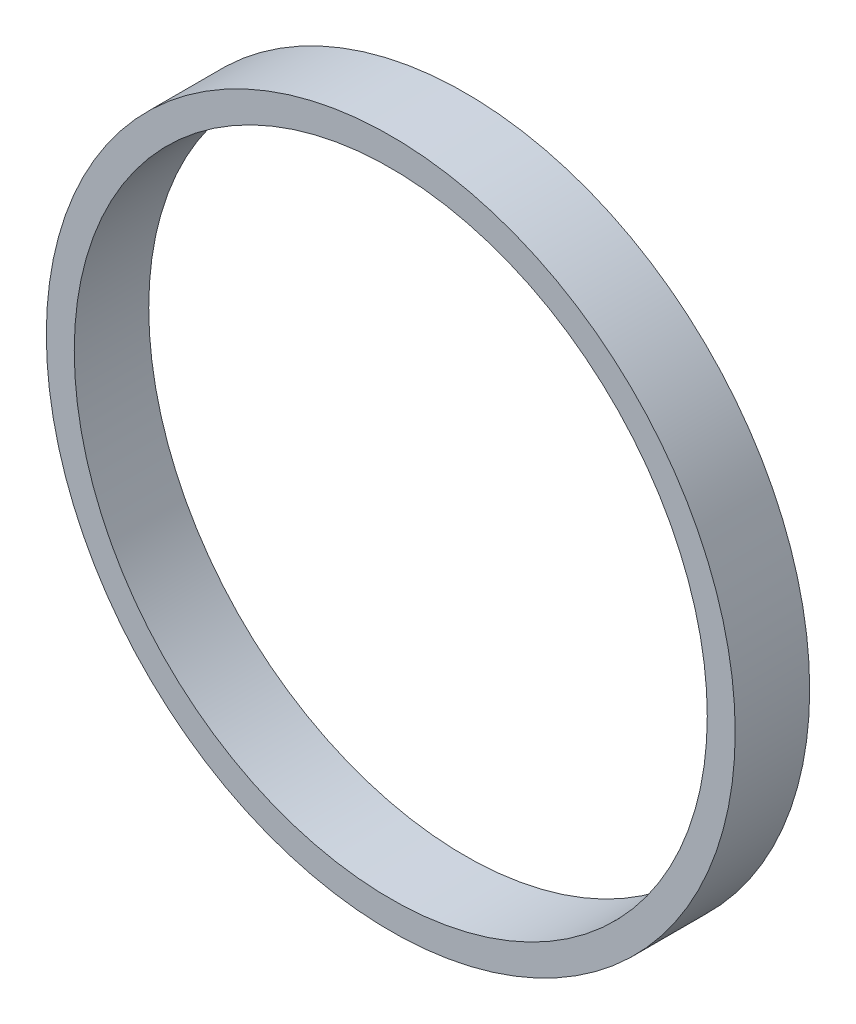
SolidWorks part; units mm, degrees
ref_plane "Front Plane" through (0, 0, 0) normal (0, 0, 1) x (1, 0, 0)
ref_plane "Top Plane" through (0, 0, 0) normal (0, 1, 0) x (1, 0, 0)
ref_plane "Right Plane" through (0, 0, 0) normal (1, 0, 0) x (0, 0, -1)
sketch "Sketch1" plane through (0, 0, 0) normal (0, 0, 1) x (1, 0, 0)
  circle A0 centre (0, 0) radius 18.5
  circle A1 centre (0, 0) radius 17
  dimension "D1" = 37
  dimension "D2" = 34
extrude "Boss-Extrude1" add sketch "Sketch1" along normal blind 4
